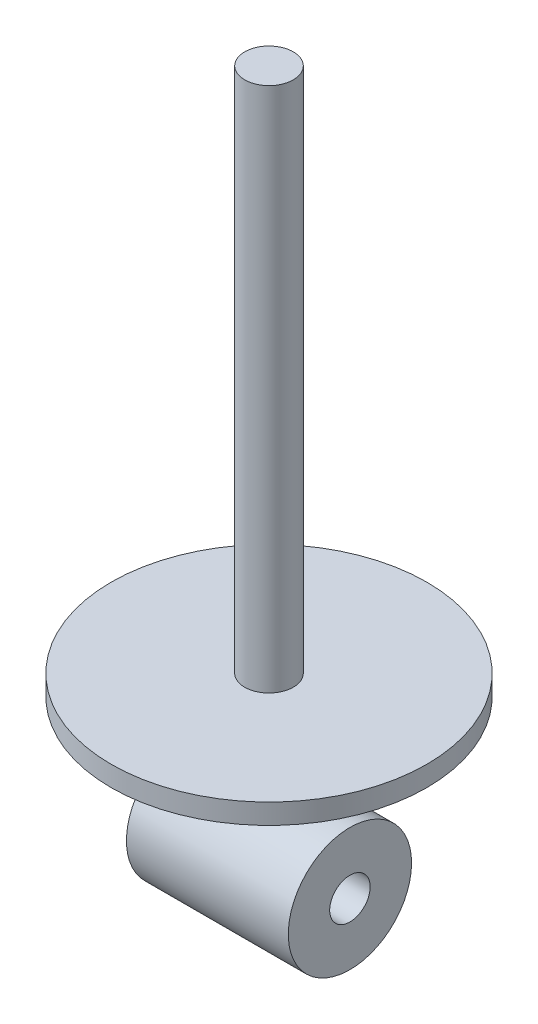
SolidWorks part; units mm, degrees
material "1060 Alloy"
ref_plane "Front Plane" through (0, 0, 0) normal (0, 0, 1) x (1, 0, 0)
ref_plane "Top Plane" through (0, 0, 0) normal (0, 1, 0) x (1, 0, 0)
ref_plane "Right Plane" through (0, 0, 0) normal (1, 0, 0) x (0, 0, -1)
sketch "Sketch4" plane through (0, 0, 0) normal (0, 1, 0) x (1, 0, 0)
  circle A0 centre (0, 0) radius 39
  dimension "D1" = 78
extrude "Boss-Extrude2" add sketch "Sketch4" along normal blind 5
sketch "Sketch5" plane through (0, 5, 0) normal (0, 1, 0) x (1, 0, 0)
  circle A0 centre (0, 0) radius 6
  dimension "D1" = 12
extrude "Boss-Extrude3" add sketch "Sketch5" along normal blind 130
sketch "Sketch6" plane through (0, 0, 0) normal (0, -1, 0) x (1, 0, 0)
  circle A0 centre (0, 0) radius 7.5
  dimension "D1" = 15
extrude "Boss-Extrude4" add sketch "Sketch6" along normal blind 20
sketch "Sketch8" plane through (0, 0, 0) normal (1, 0, 0) x (0, 0, -1)
  circle A0 centre (0, -33.2265) radius 15.2332
  circle A1 centre (0, -33.2265) radius 5
  dimension "D1" = 10
extrude "Boss-Extrude5" add sketch "Sketch8" along normal mid plane 40
